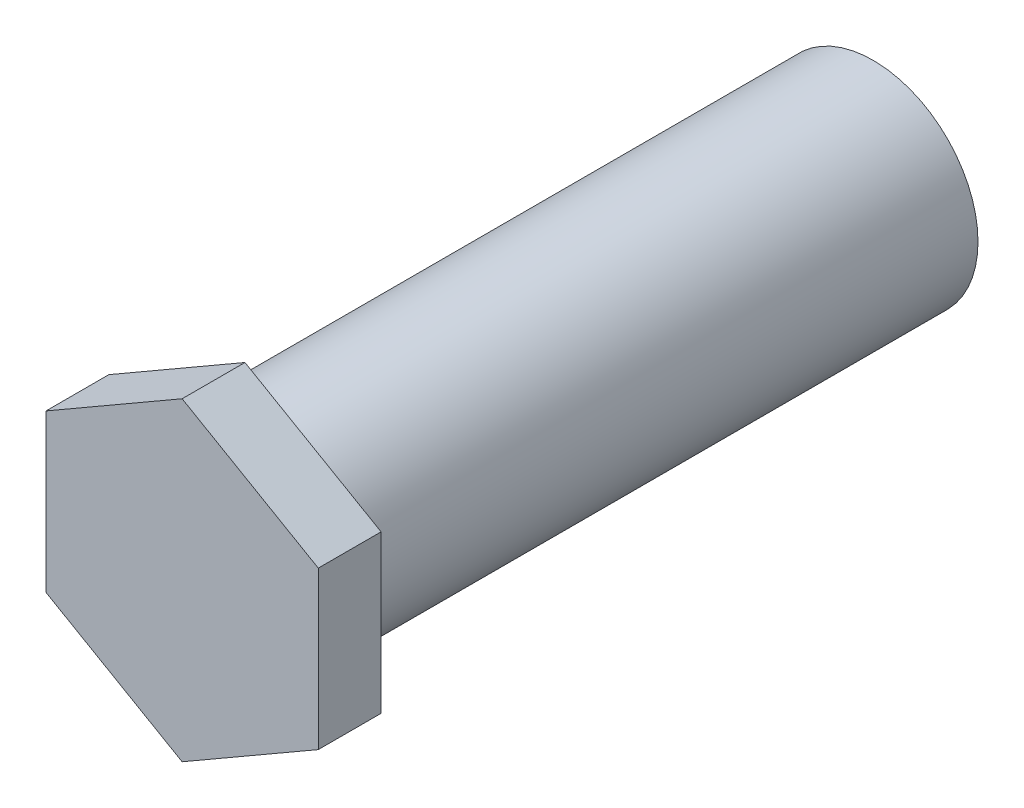
SolidWorks part; units mm, degrees
ref_plane "Front Plane" through (0, 0, 0) normal (0, 0, 1) x (1, 0, 0)
ref_plane "Top Plane" through (0, 0, 0) normal (0, 1, 0) x (1, 0, 0)
ref_plane "Right Plane" through (0, 0, 0) normal (1, 0, 0) x (0, 0, -1)
sketch "Sketch1" plane through (0, 0, 0) normal (0, 0, 1) x (1, 0, 0)
  circle A0 centre (0, 0) radius 5
  dimension "D1" = 10
extrude "Boss-Extrude1" add sketch "Sketch1" against normal blind 30
cosmetic thread "Cosmetic Thread1" parameters "D1"=20, "D2"=7.5
sketch "Sketch2" plane through (0, 0, 0) normal (0, 0, 1) x (1, 0, 0)
  line L1 (-6.5, -3.7528) -> (0, -7.5056)
  line L2 (0, -7.5056) -> (6.5, -3.7528)
  line L3 (6.5, -3.7528) -> (6.5, 3.7528)
  line L4 (6.5, 3.7528) -> (0, 7.5056)
  line L5 (0, 7.5056) -> (-6.5, 3.7528)
  line L6 (-6.5, 3.7528) -> (-6.5, -3.7528)
  circle A0 centre (0, 0) radius 6.5 construction
  dimension "D1" = 13
extrude "Boss-Extrude2" add sketch "Sketch2" along normal blind 3
